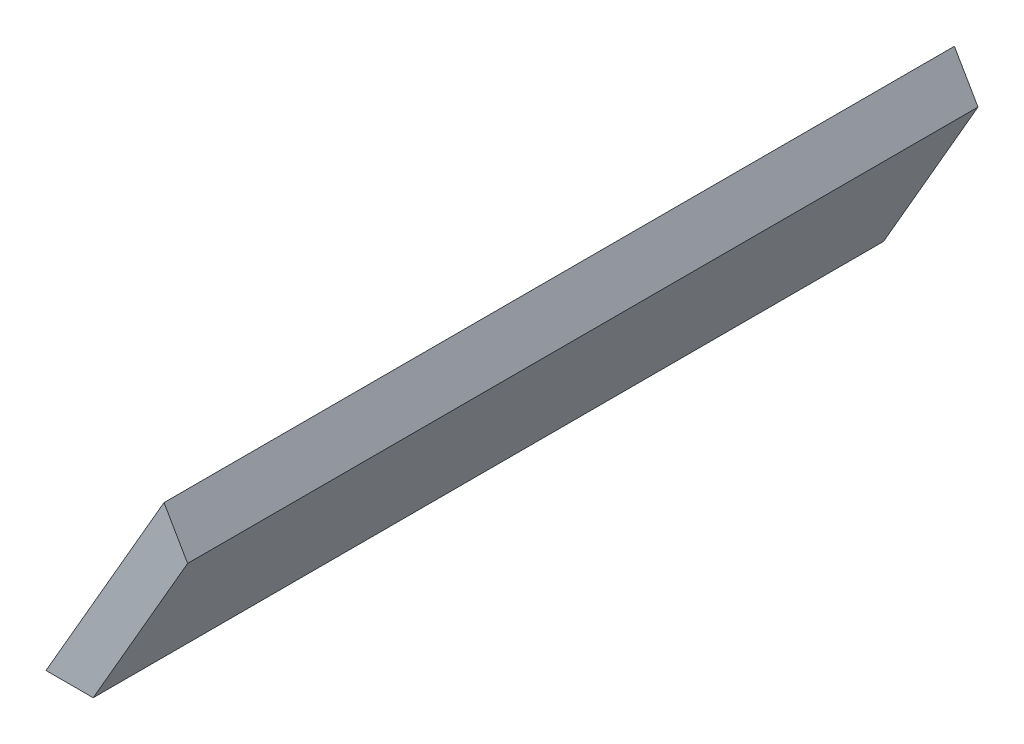
SolidWorks part; units mm, degrees
ref_plane "Plan de face" through (0, 0, 0) normal (0, 0, 1) x (1, 0, 0)
ref_plane "Plan de dessus" through (0, 0, 0) normal (0, 1, 0) x (1, 0, 0)
ref_plane "Plan de droite" through (0, 0, 0) normal (1, 0, 0) x (0, 0, -1)
sketch "Esquisse1" plane through (0, 0, 0) normal (0, 0, 1) x (1, 0, 0)
  line L0 (236.8076, 30) -> (219.4891, 0)
  line L1 (0, 30) -> (236.8076, 30)
  line L2 (0, 30) -> (0, 0)
  line L3 (0, 0) -> (236.8076, 0)
  line L4 (236.8076, 30) -> (236.8076, 0)
  line L5 (236.8076, 30) -> (254.1276, 0)
  line L6 (254.1276, 0) -> (236.8076, 0)
  line L7 (0, 30) -> (17.3185, 0)
  line L8 (17.3185, 0) -> (0, 30)
  line L9 (0, 30) -> (-17.3185, 0)
  line L10 (-17.3185, 0) -> (0, 0)
  line L11 (17.3185, 0) -> (0, -30)
  line L12 (-17.3185, 0) -> (0, -30)
  line L13 (0, -30) -> (-88.9889, -184.1513)
  line L14 (-17.3185, 0) -> (-86.5924, -120)
  line L15 (219.4891, 0) -> (236.8076, -30)
  line L16 (236.8076, -30) -> (254.1276, 0)
  line L17 (254.1276, 0) -> (323.4076, -120)
  line L18 (236.8076, -30) -> (326.5951, -185.5348)
  line L19 (323.4076, -120) -> (288.763, -120)
  line L20 (288.763, -120) -> (306.0907, -90.0053)
  line L21 (-86.5924, -120) -> (-51.9554, -120)
  line L22 (-51.9554, -120) -> (-69.2739, -90)
  line L23 (-69.2739, -90) -> (-34.637, -90)
  line L24 (306.0907, -90.0053) -> (271.4476, -90.0053)
  dimension "D1" = 30
  dimension "D3" = 34.64
  dimension "D4" = 17.3185
  dimension "D5" = 17.32
  dimension "D6" = 34.64
  dimension "D7" = 34.64
  dimension "D8" = 17.3185
  dimension "D9" = 17.3185
  dimension "D10" = 34.64
  dimension "D11" = 29.9974
  dimension "D12" = 34.64
  dimension "D13" = 34.6408
  dimension "D14" = 29.998
  dimension "D15" = 150
  dimension "D16" = 150
  dimension "D17" = 34.64
  dimension "D18" = 34.637
  dimension "D19" = 34.64
  dimension "D20" = 202.1707
  dimension "D21" = 410
  dimension "D22" = 410
  dimension "D23" = 236.8076
  dimension "D24" = 34.637
  dimension "D25" = 340.7185
extrude "Boss.-Extru.1" add sketch "Esquisse1" along normal blind 580 contours L22 L13 L12 L14 | L10 L12 L11 L3 | L9 L10 L2 | L7 L2 L3 | L23 L22 L13 | L21 L22 L14 | L17 L19 L20 L24
sketch "Esquisse2" plane through (0, 30, 0) normal (0, 1, 0) x (1, 0, 0)
  line L0 (236.8076, -580) -> (0, 0) construction
  line L1 (0, -580) -> (236.8076, 0) construction
  line L2 (118.4038, -290) -> (118.4038, 0) construction
  line L3 (0, 0) -> (236.8076, 0) construction
  line L4 (118.4038, 0) -> (118.4038, -100) construction
  circle A0 centre (118.4038, -290) radius 100
  circle A1 centre (118.4038, -100) radius 31.5
  dimension "D1" = 200
  dimension "D3" = 63
  dimension "D2" = 100
extrude "Enlèv. mat.-Extru.1" cut sketch "Esquisse2" against normal up to next
